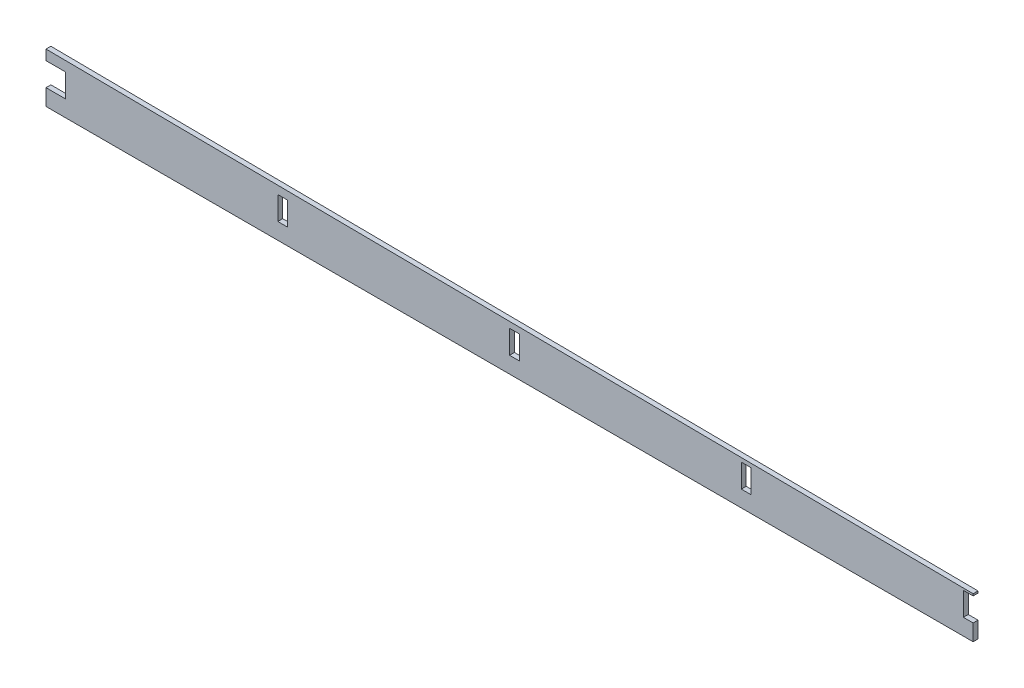
SolidWorks part; units mm, degrees
material "Balsa"
ref_plane "Front Plane" through (0, 0, 0) normal (0, 0, 1) x (1, 0, 0)
ref_plane "Top Plane" through (0, 0, 0) normal (0, 1, 0) x (1, 0, 0)
ref_plane "Right Plane" through (0, 0, 0) normal (1, 0, 0) x (0, 0, -1)
sketch "Sketch1" plane through (0, 0, 0) normal (0, 0, 1) x (1, 0, 0)
  line L0 (-62.9341, -79.3766) -> (-62.9341, -74.0554)
  line L1 (-62.9341, -74.0554) -> (-56.5841, -74.0554)
  line L2 (-56.5841, -74.0554) -> (-56.5841, -66.4354)
  line L3 (-56.5841, -66.4354) -> (-62.9341, -66.4354)
  line L4 (-62.9341, -66.4354) -> (-62.9341, -63.1495)
  line L5 (-62.9341, -63.1495) -> (239.3259, -65.8102)
  line L6 (239.3259, -65.8102) -> (239.3259, -66.4354)
  line L7 (239.3259, -66.4354) -> (236.1509, -66.4354)
  line L8 (236.1509, -66.4354) -> (236.1509, -74.0554)
  line L9 (236.1509, -74.0554) -> (239.3259, -74.0554)
  line L10 (239.3259, -74.0554) -> (239.3259, -79.3766)
  line L11 (239.3259, -79.3766) -> (-62.9341, -79.3766)
  line L12 (12.6309, -74.0554) -> (12.6309, -66.4354)
  line L13 (12.6309, -66.4354) -> (15.8059, -66.4354)
  line L14 (15.8059, -66.4354) -> (15.8059, -74.0554)
  line L15 (15.8059, -74.0554) -> (12.6309, -74.0554)
  line L16 (88.1959, -74.0554) -> (88.1959, -66.4354)
  line L17 (88.1959, -66.4354) -> (91.3709, -66.4354)
  line L18 (91.3709, -66.4354) -> (91.3709, -74.0554)
  line L19 (163.7609, -74.0554) -> (163.7609, -66.4354)
  line L20 (163.7609, -66.4354) -> (166.9359, -66.4354)
  line L21 (166.9359, -66.4354) -> (166.9359, -74.0554)
  line L22 (166.9359, -74.0554) -> (163.7609, -74.0554)
  line L23 (88.1959, -74.0554) -> (91.3709, -74.0554)
extrude "Boss-Extrude2" add sketch "Sketch1" along normal blind 1.5875
